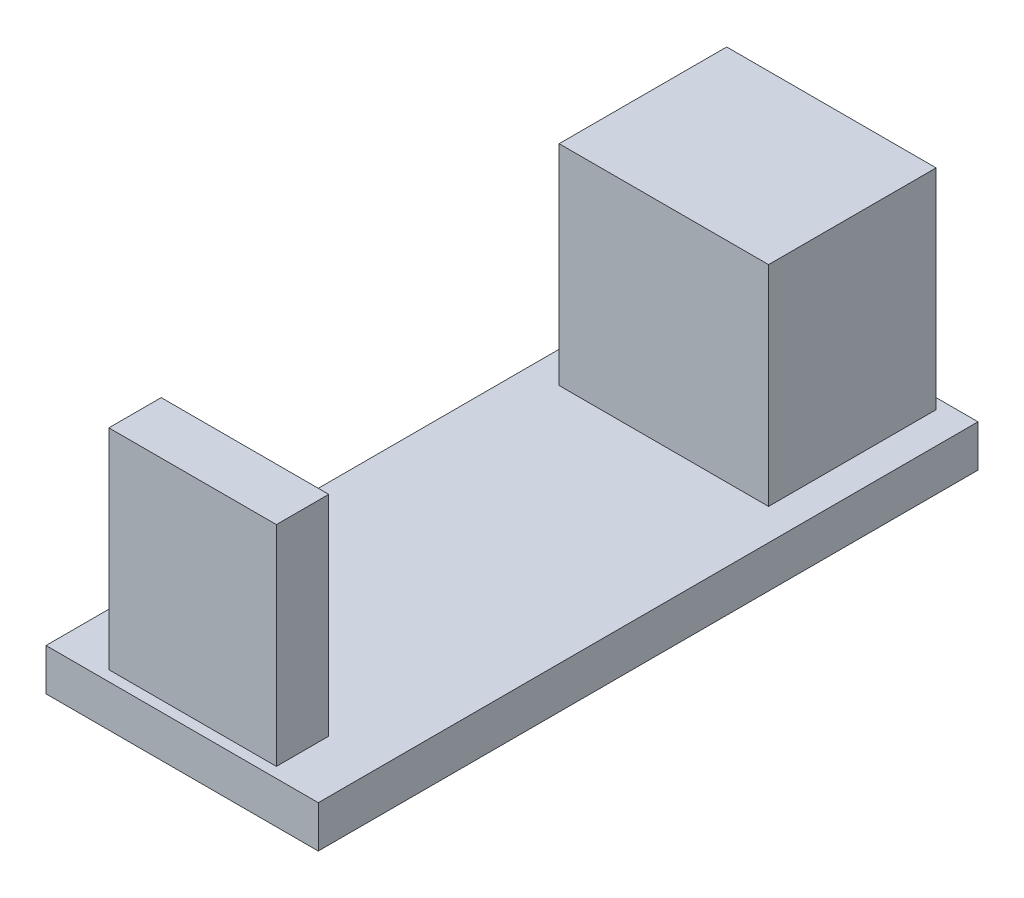
SolidWorks part; units mm, degrees
ref_plane "Plano frontal" through (0, 0, 0) normal (0, 0, 1) x (1, 0, 0)
ref_plane "Plano superior" through (0, 0, 0) normal (0, 1, 0) x (1, 0, 0)
ref_plane "Plano direito" through (0, 0, 0) normal (1, 0, 0) x (0, 0, -1)
sketch "Esboço1" plane through (0, 0, 0) normal (0, 1, 0) x (1, 0, 0)
  line L1 (-6.5, 15.75) -> (6.5, 15.75)
  line L2 (-6.5, 15.75) -> (-6.5, -15.75)
  line L3 (-6.5, -15.75) -> (6.5, -15.75)
  line L4 (6.5, 15.75) -> (6.5, -15.75)
  line L5 (-6.5, 15.75) -> (6.5, -15.75) construction
  line L6 (-6.5, -15.75) -> (6.5, 15.75) construction
  point P0 (0, 0)
  dimension "D1" = 31.5
  dimension "D2" = 13
extrude "Ressalto-extrusão1" add sketch "Esboço1" along normal blind 2
sketch "Esboço2" plane through (0, 2, 0) normal (0, 1, 0) x (1, 0, 0)
  line L0 (6.5, -15.75) -> (6.5, 15.75) construction
  line L1 (-5, 7.25) -> (5, 7.25)
  line L2 (-5, 7.25) -> (-5, 15.25)
  line L3 (-5, 15.25) -> (5, 15.25)
  line L4 (5, 7.25) -> (5, 15.25)
  line L5 (-5, 7.25) -> (5, 15.25) construction
  line L6 (-5, 15.25) -> (5, 7.25) construction
  line L7 (6.5, 15.75) -> (-6.5, 15.75) construction
  line L8 (-4, -12.75) -> (4, -12.75)
  line L9 (-4, -12.75) -> (-4, -15.25)
  line L10 (-4, -15.25) -> (4, -15.25)
  line L11 (4, -12.75) -> (4, -15.25)
  line L12 (-4, -12.75) -> (4, -15.25) construction
  line L13 (-4, -15.25) -> (4, -12.75) construction
  line L14 (-6.5, 15.75) -> (-6.5, -15.75) construction
  line L15 (-6.5, -15.75) -> (6.5, -15.75) construction
  point P0 (0, 11.25)
  point P7 (0, -14)
  dimension "D1" = 10
  dimension "D2" = 1.5
  dimension "D3" = 8
  dimension "D4" = 0.5
  dimension "D5" = 2.5
  dimension "D6" = 8
  dimension "D7" = 2.5
  dimension "D8" = 0.5
extrude "Ressalto-extrusão2" add sketch "Esboço2" along normal blind 10
